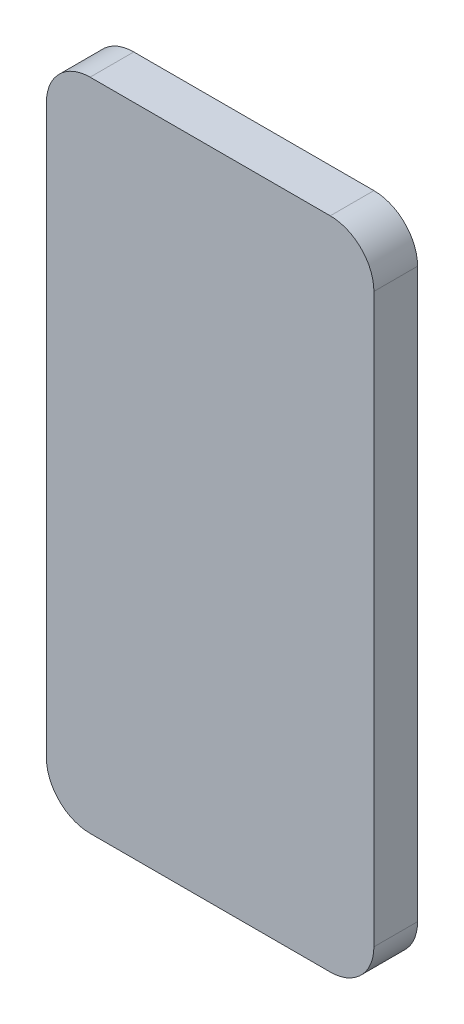
SolidWorks part; units mm, degrees
material "ABS"
ref_plane "Front Plane" through (0, 0, 0) normal (0, 0, 1) x (1, 0, 0)
ref_plane "Top Plane" through (0, 0, 0) normal (0, 1, 0) x (1, 0, 0)
ref_plane "Right Plane" through (0, 0, 0) normal (1, 0, 0) x (0, 0, -1)
sketch "Sketch2" plane through (0, 0, 0) normal (0, 0, 1) x (1, 0, 0)
  line L1 (0, 0) -> (75, 0)
  line L2 (0, 0) -> (0, 150)
  line L3 (0, 150) -> (75, 150)
  line L4 (75, 0) -> (75, 150)
  dimension "D1" = 150
  dimension "D2" = 75
extrude "Boss-Extrude2" add sketch "Sketch2" along normal blind 10
fillet "Fillet2" radius 10 4 edges at (0, 0, 5) (75, 0, 5) (75, 150, 5) (0, 150, 5)
